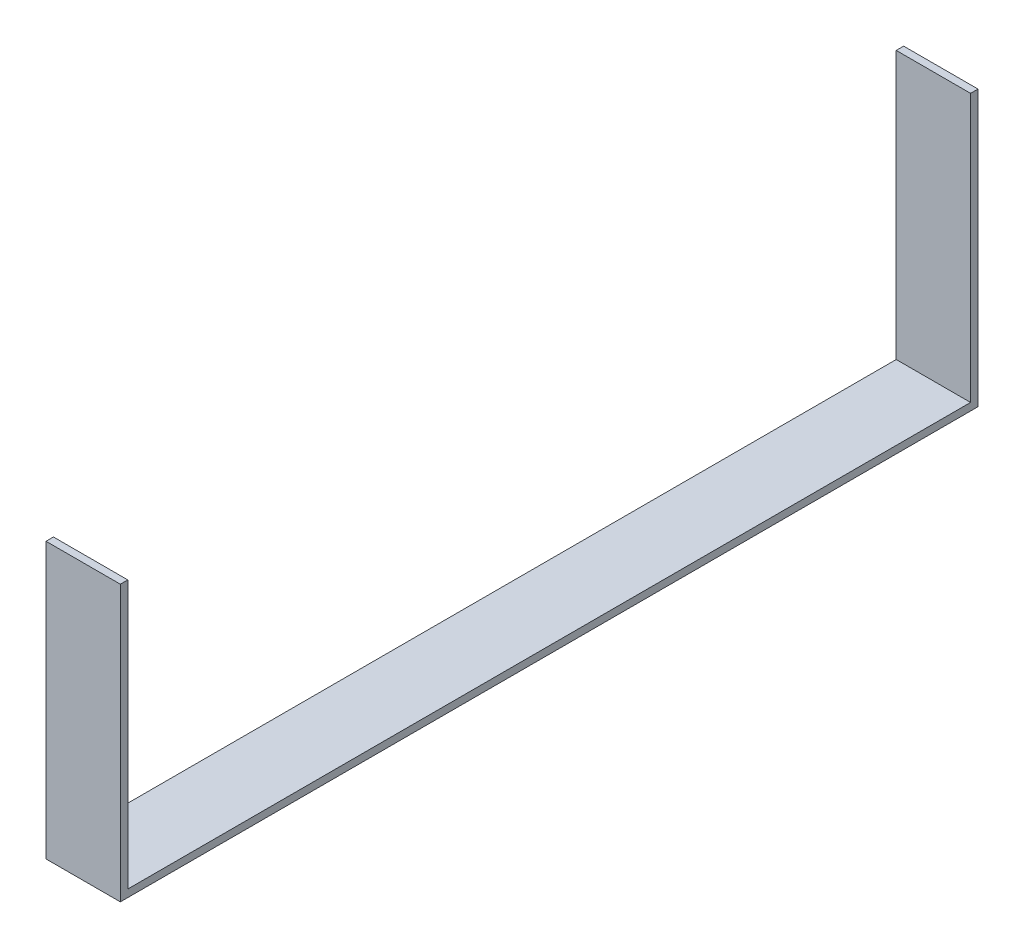
SolidWorks part; units mm, degrees
ref_plane "Front" through (0, 0, 0) normal (0, 0, 1) x (1, 0, 0)
ref_plane "Top" through (0, 0, 0) normal (0, 1, 0) x (1, 0, 0)
ref_plane "Right" through (0, 0, 0) normal (1, 0, 0) x (0, 0, -1)
sketch "Sketch1" plane through (0, 0, 0) normal (1, 0, 0) x (0, 0, -1)
  line L0 (-85, 54) -> (-85, 0)
  line L1 (-85, 0) -> (85, 0)
  line L2 (85, 0) -> (85, 54)
  line L3 (-86.5, 54) -> (-86.5, -1.5)
  line L4 (-86.5, -1.5) -> (86.5, -1.5)
  line L5 (86.5, -1.5) -> (86.5, 54)
  line L6 (-85, 54) -> (-86.5, 54)
  line L7 (85, 54) -> (86.5, 54)
  point P4 (0, 0)
  dimension "D1" = 170
  dimension "D2" = 54
  dimension "D3" = 1.5
extrude "Boss-Extrude1" add sketch "Sketch1" along normal blind 15
